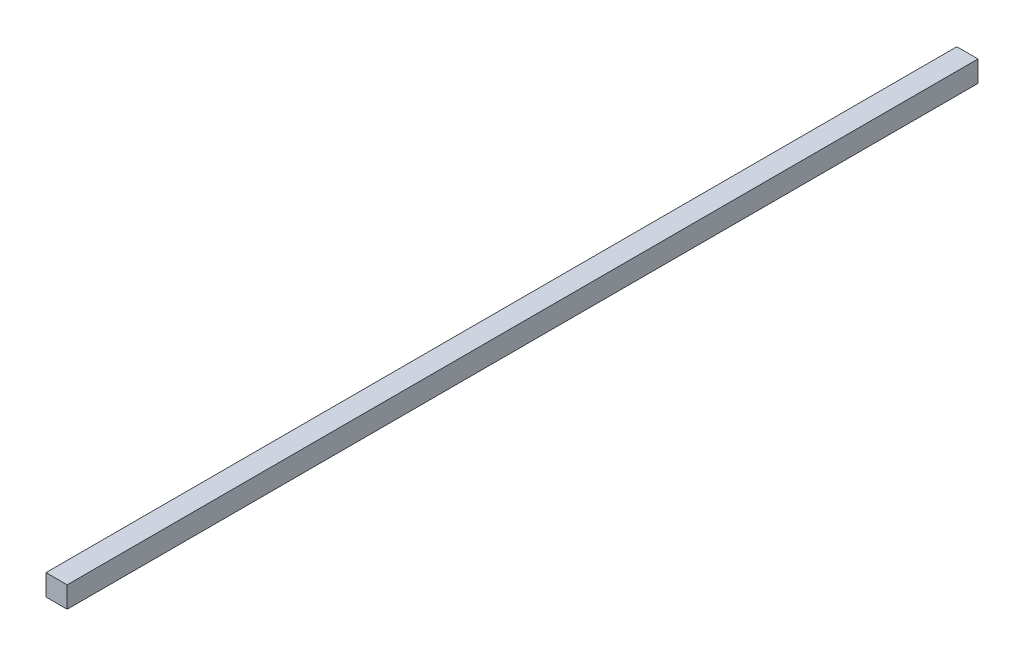
SolidWorks part; units mm, degrees
ref_plane "Front Plane" through (0, 0, 0) normal (0, 0, 1) x (1, 0, 0)
ref_plane "Top Plane" through (0, 0, 0) normal (0, 1, 0) x (1, 0, 0)
ref_plane "Right Plane" through (0, 0, 0) normal (1, 0, 0) x (0, 0, -1)
sketch "Sketch1" plane through (0, 0, 0) normal (0, 0, 1) x (1, 0, 0)
  line L1 (-10, -10) -> (10, -10)
  line L2 (-10, -10) -> (-10, 10)
  line L3 (-10, 10) -> (10, 10)
  line L4 (10, -10) -> (10, 10)
  line L5 (-10, -10) -> (10, 10) construction
  line L6 (-10, 10) -> (10, -10) construction
  point P0 (0, 0)
  dimension "D1" = 20
extrude "Boss-Extrude1" add sketch "Sketch1" along normal blind 860
sketch "Sketch2" plane through (0, 10, 0) normal (0, 1, 0) x (1, 0, 0)
  line L0 (0, -860) -> (0, 0) construction
  line L1 (10, -860) -> (-10, -860) construction
  line L2 (10, 0) -> (-10, 0) construction
ref_plane "Plane1" through (0, 0, 0) normal (-1, 0, 0) x (0, 0, 1)
